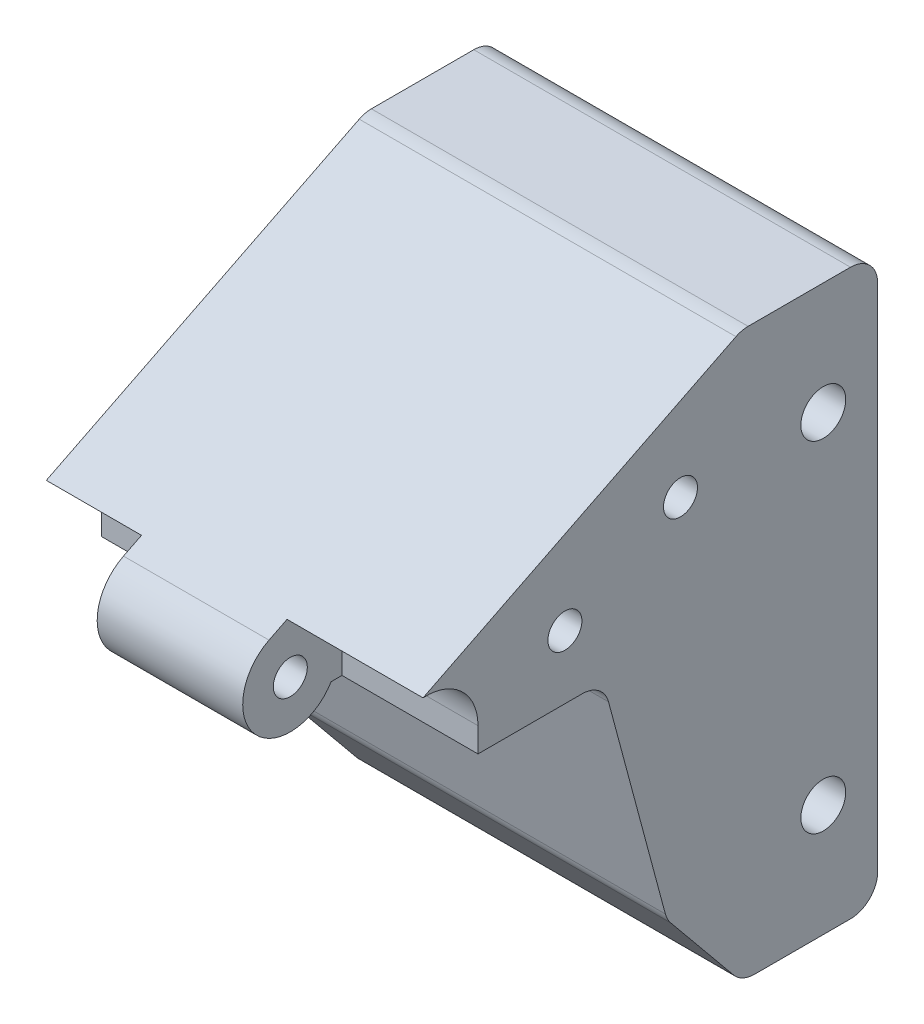
SolidWorks part; units mm, degrees
material "POM Acetal Copolymer"
ref_plane "Front" through (0, 0, 0) normal (0, 0, 1) x (1, 0, 0)
ref_plane "Top" through (0, 0, 0) normal (0, 1, 0) x (1, 0, 0)
ref_plane "Right" through (0, 0, 0) normal (1, 0, 0) x (0, 0, -1)
sketch "Sketch1" plane through (0, 0, 0) normal (0, 0, 1) x (1, 0, 0)
  line L1 (13.85, 20.75) -> (-13.85, 20.75)
  line L2 (13.85, 20.75) -> (13.85, -20.75)
  line L3 (13.85, -20.75) -> (-13.85, -20.75)
  line L4 (-13.85, 20.75) -> (-13.85, -20.75)
  line L5 (13.85, 20.75) -> (-13.85, -20.75) construction
  line L6 (13.85, -20.75) -> (-13.85, 20.75) construction
  point P0 (0, 0)
  dimension "D1" = 27.7
  dimension "D2" = 41.5
extrude "Boss-Extrude1" add sketch "Sketch1" along normal blind 10
sketch "Sketch2" plane through (0, 0, 0) normal (1, 0, 0) x (0, 0, -1)
  line L0 (-4, 20.75) -> (-4, -20.75) construction
  line L1 (-4, 0) -> (0, 0) construction
  line L4 (0, -20.75) -> (0, 20.75)
  line L5 (0, 20.75) -> (-10, 20.75)
  line L6 (-10, 20.75) -> (-10, -20.75)
  line L7 (-10, -20.75) -> (0, -20.75)
  line L8 (0, -20.75) -> (0, 20.75)
  line L9 (0, 20.75) -> (-10, 20.75)
  line L10 (-10, 20.75) -> (-10, -20.75)
  line L11 (-10, -20.75) -> (0, -20.75)
  circle A0 centre (-4, 12.5) radius 1.65
  circle A1 centre (-4, -12.5) radius 1.65
  dimension "D3" = 3.3
  dimension "D2" = 6
  dimension "D4" = 25
  dimension "D1" = 0
extrude "Cut-Extrude2" cut sketch "Sketch2" against normal through all and the other way through all contours A0 | A1
sketch "Sketch3" plane through (0, 0, 0) normal (1, 0, 0) x (0, 0, -1)
  line L0 (-10, -14.05) -> (-10, -20.75)
  line L1 (-10, -20.75) -> (-15.5, -14.05)
  line L2 (-34.7544, 8.3809) -> (-10, 20.75)
  line L3 (-10, 20.75) -> (0, 20.75) construction
  line L4 (-10, -14.05) -> (-15.5, -14.05)
  line L5 (-30.1883, 3.45) -> (-10, 3.45)
  line L6 (-10, -20.75) -> (-10, 20.75) construction
  line L8 (-10, 20.75) -> (-10, 3.45)
  line L9 (-15.5, -14.05) -> (-20.1883, 3.45)
  line L10 (-10, -14.05) -> (-10, 3.45)
  arc A0 (-34.7544, 8.3809) -> (-30.1883, 3.45) centre (-33.19, 5.25) ccw
  circle A1 centre (-33.19, 5.25) radius 1.25
  dimension "D3" = 23.19
  dimension "D4" = 15.5
  dimension "D2" = 2.5
  dimension "D1" = 3.5
  dimension "D5" = 10
  dimension "D6" = 34.8
  dimension "D7" = 5.5
  dimension "D8" = 1.8
extrude "Boss-Extrude2" add sketch "Sketch3" against normal up to surface and the other way up to surface
sketch "Sketch4" plane through (-13.85, 0, 0) normal (-1, 0, 0) x (0, 0, 1)
  line L0 (20.1883, 3.45) -> (30.1883, 3.45) construction
  line L1 (20.1883, 3.45) -> (30.1883, 3.45)
  line L2 (29.39, 3.45) -> (29.39, 5.25)
  circle A0 centre (33.19, 5.25) radius 3.5
  arc A1 (30.1883, 3.45) -> (34.7544, 8.3809) centre (33.19, 5.25) ccw construction
  circle A2 centre (33.19, 5.25) radius 3.8
  line M8 (20.1883, 3.45) -> (30.1883, 3.45)
  arc M9 (30.1883, 3.45) -> (34.7544, 8.3809) centre (33.19, 5.25) ccw
  line M10 (34.7544, 8.3809) -> (10, 20.75)
  circle M12 centre (33.19, 5.25) radius 1.25
  dimension "D1" = 0.3
extrude "Cut-Extrude3" cut sketch "Sketch4" against normal blind 7 contours A0 M9 M12 | A2 A0 M10 M8 | A2 M8 M10 M9 | A2 L2 L1
sketch "Sketch6" plane through (13.85, 0, 0) normal (1, 0, 0) x (0, 0, -1)
  line L0 (-20.1883, 3.45) -> (-30.1883, 3.45) construction
  line L1 (-29.39, 3.45) -> (-29.39, 5.25) construction
  line L2 (-20.1883, 3.45) -> (-30.1883, 3.45)
  line L3 (-29.39, 3.45) -> (-29.39, 5.25)
  circle A0 centre (-33.19, 5.25) radius 3.8 construction
  circle A1 centre (-33.19, 5.25) radius 3.8
  line M5 (-10, 20.75) -> (-34.7544, 8.3809)
  arc M6 (-34.7544, 8.3809) -> (-30.1883, 3.45) centre (-33.19, 5.25) ccw
  line M7 (-30.1883, 3.45) -> (-20.1883, 3.45)
  circle M11 centre (-33.19, 5.25) radius 1.25
extrude "Cut-Extrude5" cut sketch "Sketch6" against normal blind 10 contours A1 M5 M7 M6 | A1 M7 M5 M6 M11 | A1 L2 L3
sketch "Sketch5" plane through (-13.85, 0, 0) normal (-1, 0, 0) x (0, 0, 1)
  line L0 (22.9992, 8.1063) -> (14.5, 12.3531) construction
  line L1 (10, 20.75) -> (33.4306, 9.0424) construction
  line L2 (10, 20.75) -> (10, 3.45)
  line L3 (10, 3.45) -> (20.1883, 3.45)
  line L4 (20.1883, 3.45) -> (29.39, 3.45) construction
  line L5 (20.1883, 3.45) -> (15.5, -14.05) construction
  circle A0 centre (14.5, 12.3531) radius 1.25
  circle A1 centre (22.9992, 8.1063) radius 1.25
  dimension "D1" = 2.5
  dimension "D2" = 4.5
  dimension "D3" = 5.5
  dimension "D4" = 7
extrude "Cut-Extrude4" cut sketch "Sketch5" against normal through all
fillet "Fillet1" radius 2 6 edges at (0, -20.75, 0) (0, 3.45, 20.1883) (0, 20.75, 0) (0, 20.75, 10) (0, -20.75, 10) (0, -14.05, 15.5)
